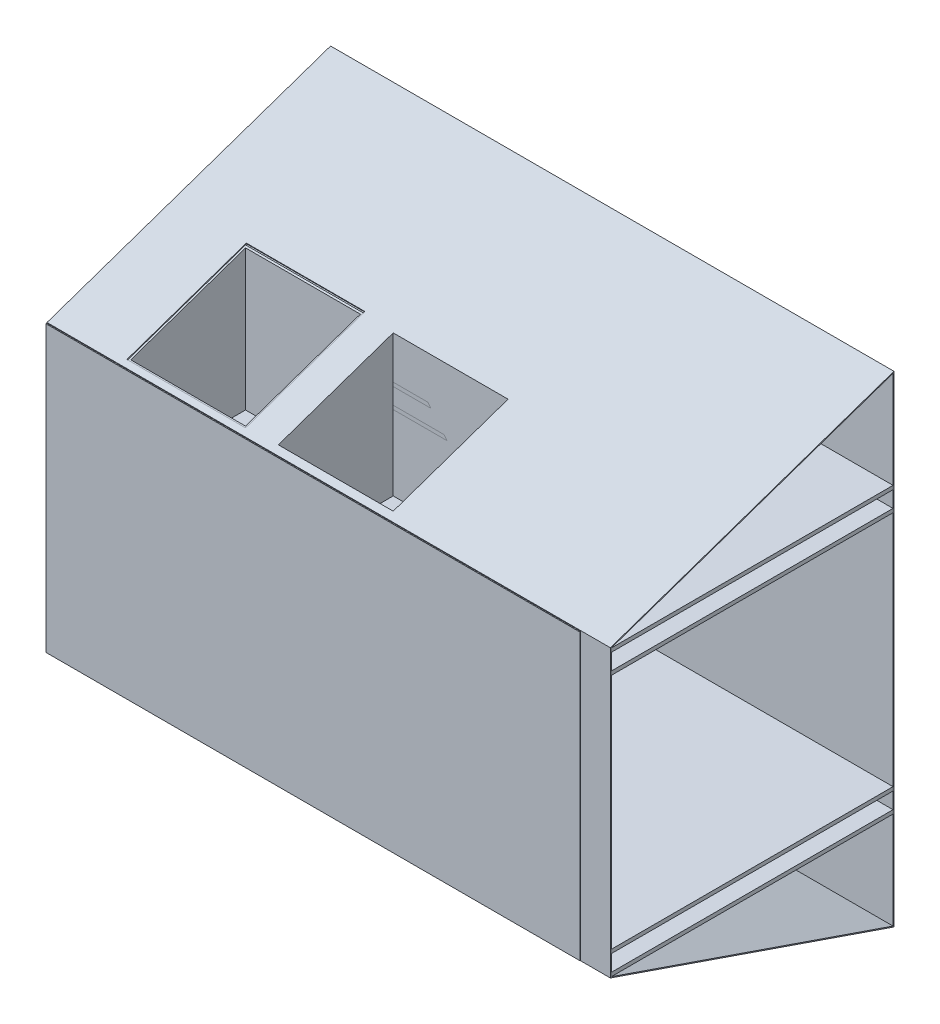
SolidWorks part; units mm, degrees
material "Stainless Steel 2205"
ref_plane "Front Plane" through (0, 0, 0) normal (0, 0, 1) x (1, 0, 0)
ref_plane "Top Plane" through (0, 0, 0) normal (0, 1, 0) x (1, 0, 0)
ref_plane "Right Plane" through (0, 0, 0) normal (1, 0, 0) x (0, 0, -1)
sketch "Sketch1" plane through (0, 0, 0) normal (0, 0, 1) x (1, 0, 0)
  line L1 (0, 0) -> (1800, 0)
  line L2 (0, 0) -> (0, -960)
  line L3 (0, -960) -> (1800, -960)
  line L4 (1800, 0) -> (1800, -960)
  point P5 (0, 0)
  dimension "D1" = 1800
  dimension "D2" = 960
extrude "Boss-Extrude1" add sketch "Sketch1" along normal blind 6.35
sketch "Sketch2" plane through (0, 0, 0) normal (1, 0, 0) x (0, 0, -1)
  line L0 (0, 0) -> (950, 327.1112)
  line L1 (950, 327.1112) -> (950, -1287.1112)
  line L2 (950, -1287.1112) -> (0, -960)
  line L3 (0, -960) -> (0, 0)
  line L4 (-3.175, -962.2647) -> (-3.175, 2.2647)
  line L5 (-3.175, 2.2647) -> (953.175, 331.5624)
  line L6 (953.175, 331.5624) -> (953.175, -1291.5624)
  line L7 (953.175, -1291.5624) -> (-3.175, -962.2647)
  dimension "D2" = 71
  dimension "D3" = 71
  dimension "D4" = 950
  dimension "D1" = 3.175
extrude "Boss-Extrude2" add sketch "Sketch2" along normal blind 1900
sketch "Sketch4" plane through (0, 0, 0) normal (0, 1, 0) x (1, 0, 0)
  line L0 (0, 953.175) -> (0, -3.175) construction
  line L1 (249.6312, 417.8713) -> (649.6312, 417.8713)
  line L2 (249.6312, 417.8713) -> (249.6312, 17.8713)
  line L3 (249.6312, 17.8713) -> (649.6312, 17.8713)
  line L4 (649.6312, 417.8713) -> (649.6312, 17.8713)
  dimension "D1" = 400
  dimension "D2" = 400
  dimension "D3" = 249.6312
curve "Curve1"
sketch "Sketch6" plane through (0, 3.002, 1.0337) normal (0, 0.9455, 0.3256) x (1, 0, 0)
  line L0 (649.6312, 441.9494) -> (649.6312, 18.9011) construction
  line L1 (649.6312, 444.6894) -> (249.6312, 444.6894)
  line L2 (649.6312, 444.6894) -> (649.6312, 18.9011)
  line L3 (649.6312, 18.9011) -> (249.6312, 18.9011)
  line L4 (249.6312, 444.6894) -> (249.6312, 18.9011)
  line L5 (649.6312, 18.9011) -> (249.6312, 18.9011) construction
extrude "Cut-Extrude1" cut sketch "Sketch6" against normal blind 300
sketch "Sketch7" plane through (0, -861.2472, 296.5512) normal (0, -0.9455, 0.3256) x (1, 0, 0)
  line L0 (249.6312, -331.4465) -> (249.6312, -754.4948) construction
  line L1 (249.6312, -796.9701) -> (649.6312, -796.9701)
  line L2 (249.6312, -796.9701) -> (249.6312, -371.299)
  line L3 (249.6312, -371.299) -> (649.6312, -371.299)
  line L4 (649.6312, -796.9701) -> (649.6312, -371.299)
  line L5 (649.6312, -754.4948) -> (649.6312, -331.4465) construction
extrude "Cut-Extrude2" cut sketch "Sketch7" against normal blind 300
sketch "Sketch8" plane through (0, 0, 0) normal (0, 1, 0) x (1, 0, 0)
  line L0 (255.9812, 23.1876) -> (255.9812, 410.4876)
  line L1 (249.6312, 16.8376) -> (649.6312, 16.8376)
  line L2 (249.6312, 16.8376) -> (249.6312, 416.8376)
  line L3 (249.6312, 416.8376) -> (649.6312, 416.8376)
  line L4 (649.6312, 16.8376) -> (649.6312, 416.8376)
  line L5 (255.9812, 410.4876) -> (643.2812, 410.4876)
  line L6 (643.2812, 23.1876) -> (643.2812, 410.4876)
  line L7 (255.9812, 23.1876) -> (643.2812, 23.1876)
  dimension "D1" = 6.35
extrude "Boss-Extrude4" add sketch "Sketch8" against normal up to surface and the other way up to surface separate body up to face at (449.6312, -1048.4208, -256.7926) other way up to face at (449.6312, 75.4651, -219.1667)
sketch "Sketch11" plane through (0, 0, -953.175) normal (0, 0, -1) x (-1, 0, 0)
  line L2 (-1900, 331.5624) -> (0, 331.5624) construction
  line L3 (0, -1291.5624) -> (0, 331.5624) construction
  circle A1 centre (-350, -492.2076) radius 131.35
  dimension "D1" = 823.77
  dimension "D2" = 350
extrude "Boss-Extrude6" add sketch "Sketch11" against normal blind 30
sketch "Sketch12" plane through (0, 0, -953.175) normal (0, 0, -1) x (-1, 0, 0)
  line L0 (0, -1291.5624) -> (0, 331.5624) construction
  line L2 (-1900, 331.5624) -> (0, 331.5624) construction
  circle A0 centre (-350, -492.2076) radius 125
  dimension "D1" = 250
  dimension "D2" = 350
  dimension "D3" = 823.77
extrude "Cut-Extrude5" cut sketch "Sketch12" against normal blind 20
sketch "Sketch14" plane through (0, 0, 0) normal (0, 1, 0) x (1, 0, 0)
  line L0 (649.6312, 417.8713) -> (649.6312, 17.8713) construction
  line L1 (749.6312, 412.7618) -> (1149.6312, 412.7618)
  line L2 (749.6312, 412.7618) -> (749.6312, 12.7618)
  line L3 (749.6312, 12.7618) -> (1149.6312, 12.7618)
  line L4 (1149.6312, 412.7618) -> (1149.6312, 12.7618)
  line L5 (755.9812, 406.4118) -> (1143.2812, 406.4118)
  line L6 (1143.2812, 406.4118) -> (1143.2812, 19.1118)
  line L7 (755.9812, 19.1118) -> (1143.2812, 19.1118)
  line L8 (755.9812, 406.4118) -> (755.9812, 19.1118)
  dimension "D1" = 400
  dimension "D2" = 400
  dimension "D3" = 100
  dimension "D4" = 6.35
extrude "Boss-Extrude7" add sketch "Sketch14" along normal up to next and the other way up to next
sketch "Sketch15" plane through (0, 0, 0) normal (0, 1, 0) x (1, 0, 0)
  line L5 (755.9812, 408.5123) -> (1143.2812, 408.5123)
  line L6 (1143.2812, 408.5123) -> (1143.2812, 21.2123)
  line L7 (755.9812, 21.2123) -> (1143.2812, 21.2123)
  line L8 (755.9812, 408.5123) -> (755.9812, 21.2123)
extrude "Cut-Extrude6" cut sketch "Sketch15" against normal up to next and the other way up to next
sketch "Sketch16" plane through (249.6312, 0, 0) normal (-1, 0, 0) x (0, 0, 1)
  line L0 (-416.8376, -1103.5287) -> (-416.8376, 143.5287) construction
  line L1 (-416.8376, -332.1987) -> (-16.8376, -332.1987)
  line L2 (-416.8376, -332.1987) -> (-416.8376, -532.1987)
  line L3 (-416.8376, -532.1987) -> (-16.8376, -532.1987)
  line L4 (-16.8376, -332.1987) -> (-16.8376, -532.1987)
  line L5 (-16.8376, -965.7977) -> (-16.8376, 5.7977) construction
  dimension "D1" = 200
  dimension "D2" = 571.33
extrude "Cut-Extrude8" cut sketch "Sketch16" against normal blind 940
sketch "Sketch18" plane through (1149.6312, 0, 0) normal (1, 0, 0) x (0, 0, -1)
  line L0 (12.7618, -964.3942) -> (12.7618, 4.3942) construction
  line L1 (16.8376, -532.1987) -> (12.7618, -532.1987)
  line L2 (16.8376, -532.1987) -> (16.8376, -410.1274)
  line L3 (16.8376, -410.1274) -> (12.7618, -410.1274)
  line L4 (12.7618, -532.1987) -> (12.7618, -410.1274)
extrude "Cut-Extrude9" cut sketch "Sketch18" against normal blind 410
sketch "Sketch19" plane through (0, -332.1987, 0) normal (0, -1, 0) x (1, 0, 0)
  line L1 (1143.2812, -21.2123) -> (755.9812, -21.2123)
  line L2 (1143.2812, -21.2123) -> (1143.2812, -408.5123)
  line L3 (1143.2812, -408.5123) -> (755.9812, -408.5123)
  line L4 (755.9812, -21.2123) -> (755.9812, -408.5123)
extrude "Boss-Extrude22" add sketch "Sketch19" along normal blind 10 separate body
sketch "Sketch22" plane through (0, -532.1987, 0) normal (0, 1, 0) x (1, 0, 0)
  line L1 (1143.2812, 408.5123) -> (755.9812, 408.5123)
  line L2 (1143.2812, 408.5123) -> (1143.2812, 19.1118)
  line L3 (1143.2812, 19.1118) -> (755.9812, 19.1118)
  line L4 (755.9812, 408.5123) -> (755.9812, 19.1118)
extrude "Boss-Extrude24" add sketch "Sketch22" along normal blind 10 separate body
sketch "Sketch23" plane through (0, -532.1987, 0) normal (0, 1, 0) x (1, 0, 0)
  line L1 (643.2812, 410.4876) -> (255.9812, 410.4876)
  line L2 (643.2812, 410.4876) -> (643.2812, 23.1876)
  line L3 (643.2812, 23.1876) -> (255.9812, 23.1876)
  line L4 (255.9812, 410.4876) -> (255.9812, 23.1876)
extrude "Boss-Extrude25" add sketch "Sketch23" along normal blind 10 separate body
sketch "Sketch24" plane through (0, -332.1987, 0) normal (0, -1, 0) x (1, 0, 0)
  line L1 (643.2812, -23.1876) -> (255.9812, -23.1876)
  line L2 (643.2812, -23.1876) -> (643.2812, -410.4876)
  line L3 (643.2812, -410.4876) -> (255.9812, -410.4876)
  line L4 (255.9812, -23.1876) -> (255.9812, -410.4876)
extrude "Boss-Extrude26" add sketch "Sketch24" along normal blind 10 separate body
sketch "Sketch25" plane through (0, 0, 0) normal (1, 0, 0) x (0, 0, -1)
  line L0 (950, -1287.1112) -> (950, 327.1112) construction
  line L1 (0, 0) -> (950, 0)
  line L2 (0, 0) -> (0, -80)
  line L3 (0, -80) -> (950, -80)
  line L4 (950, 0) -> (950, -80)
  line L5 (950, -1287.1112) -> (950, 327.1112) construction
  line L6 (0, -960) -> (950, -960)
  line L7 (0, -960) -> (0, -880)
  line L8 (0, -880) -> (950, -880)
  line L9 (950, -960) -> (950, -880)
  line L10 (0, -67.3) -> (950, -67.3)
  line L11 (0, -67.3) -> (0, -12.7)
  line L12 (0, -12.7) -> (950, -12.7)
  line L13 (950, -67.3) -> (950, -12.7)
  line L15 (0, -892.7) -> (950, -892.7)
  line L16 (0, -892.7) -> (0, -947.3)
  line L17 (0, -947.3) -> (950, -947.3)
  line L18 (950, -892.7) -> (950, -947.3)
  dimension "D1" = 80
  dimension "D2" = 80
  dimension "D3" = 12.7
  dimension "D4" = 12.7
  dimension "D5" = 12.7
  dimension "D6" = 12.7
extrude "Boss-Extrude27" add sketch "Sketch25" along normal blind 1900 contours L17 L7 L6 L9 | L7 L15 L9 L8 | L10 L2 L3 L4 | L2 L12 L4 L1
sketch "Sketch26" plane through (0, 0, 0) normal (0, 1, 0) x (1, 0, 0)
  line L1 (643.2812, 410.4876) -> (255.9812, 410.4876)
  line L2 (643.2812, 410.4876) -> (643.2812, 23.1876)
  line L3 (643.2812, 23.1876) -> (255.9812, 23.1876)
  line L4 (255.9812, 410.4876) -> (255.9812, 23.1876)
extrude "Cut-Extrude10" cut sketch "Sketch26" against normal blind 300
sketch "Sketch27" plane through (0, 0, 0) normal (0, 1, 0) x (1, 0, 0)
  line L1 (1143.2812, 408.5123) -> (755.9812, 408.5123)
  line L2 (1143.2812, 408.5123) -> (1143.2812, 21.2123)
  line L3 (1143.2812, 21.2123) -> (755.9812, 21.2123)
  line L4 (755.9812, 408.5123) -> (755.9812, 21.2123)
extrude "Cut-Extrude11" cut sketch "Sketch27" against normal blind 300
sketch "Sketch28" plane through (0, -960, 0) normal (0, -1, 0) x (1, 0, 0)
  line L1 (1143.2812, -21.2123) -> (755.9812, -21.2123)
  line L2 (1143.2812, -21.2123) -> (1143.2812, -408.5123)
  line L3 (1143.2812, -408.5123) -> (755.9812, -408.5123)
  line L4 (755.9812, -21.2123) -> (755.9812, -408.5123)
extrude "Cut-Extrude12" cut sketch "Sketch28" against normal blind 300
sketch "Sketch29" plane through (0, -960, 0) normal (0, -1, 0) x (1, 0, 0)
  line L1 (643.2812, -23.1876) -> (255.9812, -23.1876)
  line L2 (643.2812, -23.1876) -> (643.2812, -410.4876)
  line L3 (643.2812, -410.4876) -> (255.9812, -410.4876)
  line L4 (255.9812, -23.1876) -> (255.9812, -410.4876)
extrude "Cut-Extrude13" cut sketch "Sketch29" against normal blind 300
